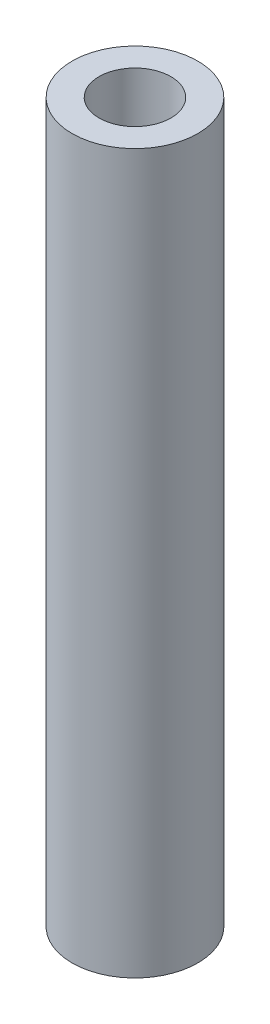
SolidWorks part; units mm, degrees
ref_plane "Alzado" through (0, 0, 0) normal (0, 0, 1) x (1, 0, 0)
ref_plane "Planta" through (0, 0, 0) normal (0, 1, 0) x (1, 0, 0)
ref_plane "Vista lateral" through (0, 0, 0) normal (1, 0, 0) x (0, 0, -1)
sketch "Croquis1" plane through (0, 0, 0) normal (0, 1, 0) x (1, 0, 0)
  circle A0 centre (0, 0) radius 2
  circle A1 centre (0, 0) radius 3.5
  dimension "D1" = 7
  dimension "D2" = 4
extrude "Saliente-Extruir1" add sketch "Croquis1" along normal blind 40
